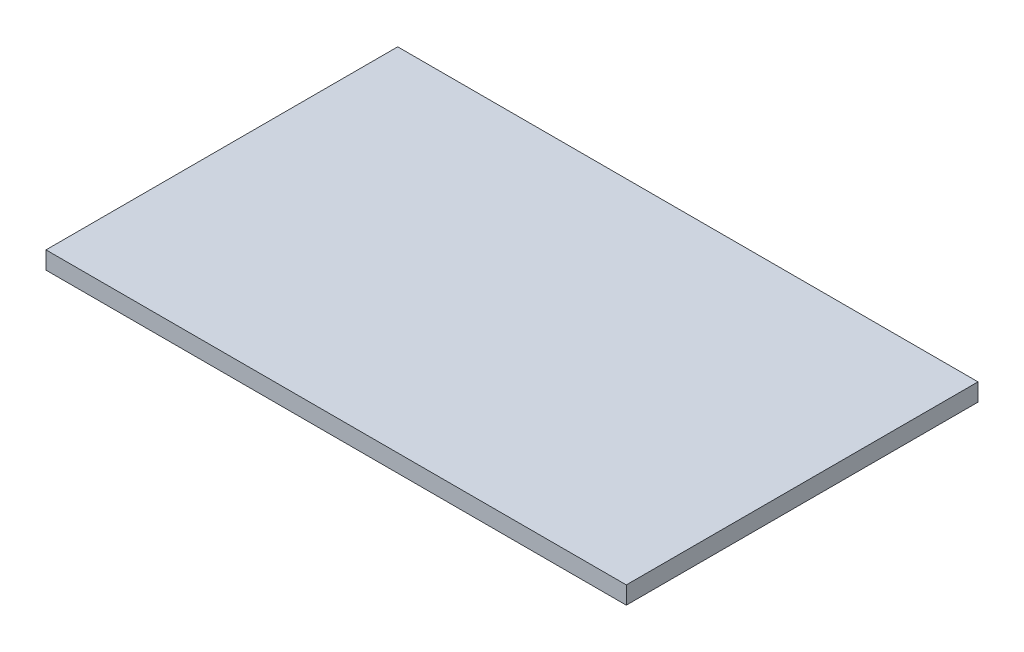
SolidWorks part; units mm, degrees
ref_plane "Plan de face" through (0, 0, 0) normal (0, 0, 1) x (1, 0, 0)
ref_plane "Plan de dessus" through (0, 0, 0) normal (0, 1, 0) x (1, 0, 0)
ref_plane "Plan de droite" through (0, 0, 0) normal (1, 0, 0) x (0, 0, -1)
sketch "Esquisse1" plane through (0, 0, 0) normal (0, 1, 0) x (1, 0, 0)
  line L1 (1.65, -1) -> (-1.65, -1)
  line L2 (1.65, -1) -> (1.65, 1)
  line L3 (1.65, 1) -> (-1.65, 1)
  line L4 (-1.65, -1) -> (-1.65, 1)
  line L5 (1.65, -1) -> (-1.65, 1) construction
  line L6 (1.65, 1) -> (-1.65, -1) construction
  point P0 (0, 0)
  dimension "D1" = 3.3
  dimension "D2" = 2
extrude "Boss.-Extru.1" add sketch "Esquisse1" along normal blind 0.1
